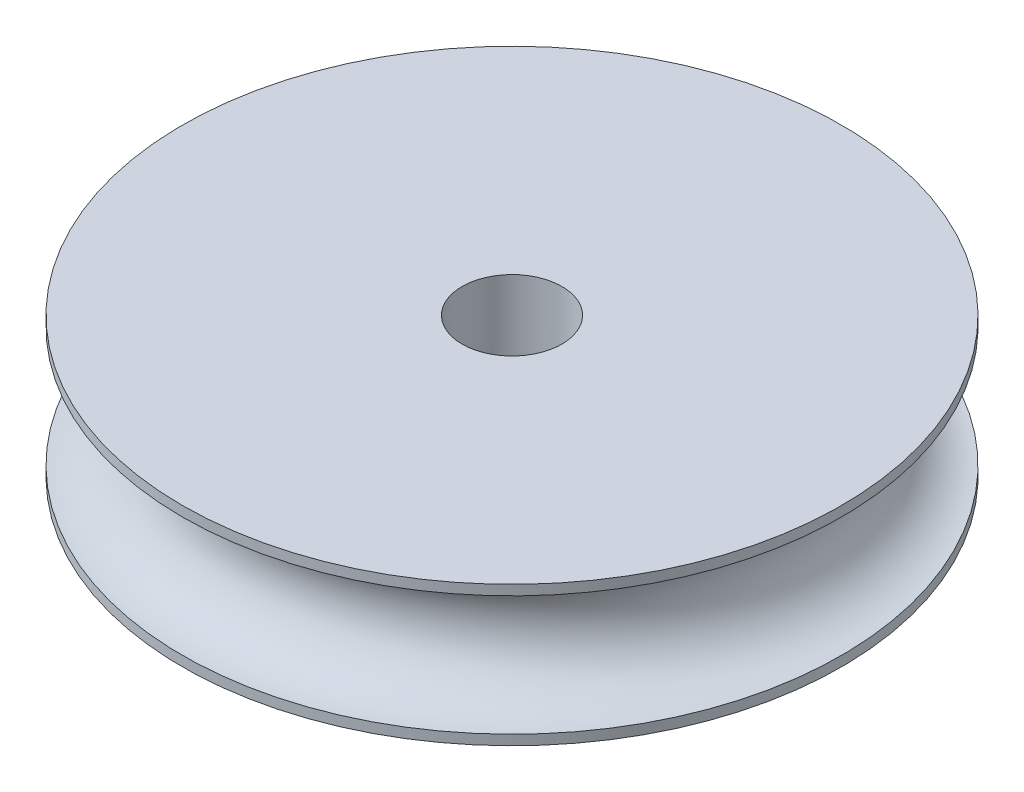
SolidWorks part; units mm, degrees
ref_plane "Front Plane" through (0, 0, 0) normal (0, 0, 1) x (1, 0, 0)
ref_plane "Top Plane" through (0, 0, 0) normal (0, 1, 0) x (1, 0, 0)
ref_plane "Right Plane" through (0, 0, 0) normal (1, 0, 0) x (0, 0, -1)
sketch "Sketch1" plane through (0, 0, 0) normal (0, 0, 1) x (1, 0, 0)
  line L0 (13.5, 6) -> (22.418, 6) construction
  line L1 (0, 0) -> (13.5, 0)
  line L2 (0, 0) -> (0, 6)
  line L3 (0, 6) -> (13.5, 6)
  line L4 (13.5, 0) -> (13.5, 6)
  line L5 (13.5, 0) -> (22.418, 0) construction
  line L6 (13.5, 6) -> (13.5, 0) construction
  line L7 (13.5, 12) -> (13.5, 0)
  line L8 (13.5, 6) -> (13.5, 0) construction
  line L9 (13.5, 12) -> (13.5, 0)
  line L10 (13.5, 3) -> (21.2573, 3)
  line L11 (13.5, 6) -> (16.5, 6)
  line L12 (13.5, 0) -> (16.5, 0)
  circle A0 centre (16.5, 3) radius 3
  point P10 (13.5, 6)
  point P11 (13.5, 6)
revolve "Revolve1" add sketch "Sketch1" angle 360 about L2
sketch "Sketch2" plane through (0, 6, 0) normal (0, 1, 0) x (1, 0, 0)
  circle A0 centre (0, 0) radius 16.5
extrude "Boss-Extrude1" add sketch "Sketch2" along normal blind 0.5
sketch "Sketch3" plane through (0, 0, 0) normal (0, -1, 0) x (1, 0, 0)
  circle A0 centre (0, 0) radius 16.5
extrude "Boss-Extrude2" add sketch "Sketch3" along normal blind 0.5
sketch "Sketch4" plane through (0, -0.5, 0) normal (0, -1, 0) x (1, 0, 0)
  circle A0 centre (0, 0) radius 1
extrude "Cut-Extrude1" cut sketch "Sketch4" against normal up to surface (7 mm away) up to face at (0, 6.5, 16.5)
sketch "Sketch5" plane through (0, 6.5, 0) normal (0, 1, 0) x (1, 0, 0)
  circle A0 centre (0, 0) radius 2.5
extrude "Cut-Extrude2" cut sketch "Sketch5" against normal blind 10
